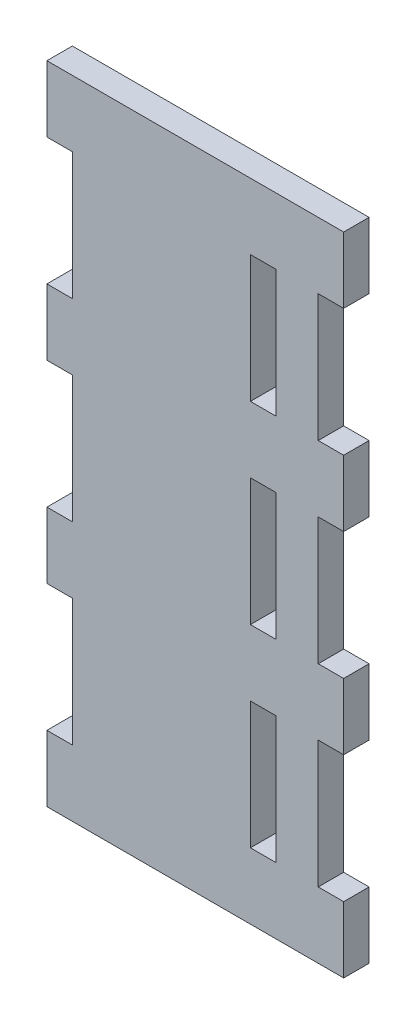
SolidWorks part; units mm, degrees
material "Oak"
ref_plane "Front Plane" through (0, 0, 0) normal (0, 0, 1) x (1, 0, 0)
ref_plane "Top Plane" through (0, 0, 0) normal (0, 1, 0) x (1, 0, 0)
ref_plane "Right Plane" through (0, 0, 0) normal (1, 0, 0) x (0, 0, -1)
sketch "Sketch1" plane through (0, 0, 0) normal (0, 0, 1) x (1, 0, 0)
  line L1 (-40.9935, 16.542) -> (-5.9935, 16.542)
  line L2 (-40.9935, 16.542) -> (-40.9935, -59.658)
  line L3 (-40.9935, -59.658) -> (-5.9935, -59.658)
  line L4 (-5.9935, 16.542) -> (-5.9935, -59.658)
  dimension "D1" = 76.2
  dimension "D2" = 35
extrude "Boss-Extrude1" add sketch "Sketch1" along normal blind 3
sketch "Sketch2" plane through (0, 0, 3) normal (0, 0, 1) x (1, 0, 0)
  line L0 (-40.9935, 16.542) -> (-40.9935, -59.658) construction
  line L1 (-40.9935, 8.742) -> (-37.9935, 8.742)
  line L2 (-40.9935, 8.742) -> (-40.9935, -6.258)
  line L3 (-40.9935, -6.258) -> (-37.9935, -6.258)
  line L4 (-37.9935, 8.742) -> (-37.9935, -6.258)
  line L5 (-5.9935, 16.542) -> (-40.9935, 16.542) construction
  line L6 (-5.9935, -59.658) -> (-5.9935, 16.542) construction
  line L7 (-5.9935, 8.742) -> (-8.9935, 8.742)
  line L8 (-5.9935, 8.742) -> (-5.9935, -6.258)
  line L9 (-5.9935, -6.258) -> (-8.9935, -6.258)
  line L10 (-8.9935, 8.742) -> (-8.9935, -6.258)
  point P8 (-39.4935, 8.742)
  dimension "D1" = 3
  dimension "D2" = 7.8
  dimension "D3" = 15
  dimension "D4" = 3
  dimension "D5" = 7.8
  dimension "D6" = 15
extrude "Cut-Extrude1" cut sketch "Sketch2" against normal through all
pattern_linear "LPattern1" count 3 spacing 22.8 along (0, -1, 0) of "Cut-Extrude1"
sketch "Sketch3" plane through (0, 0, 3) normal (0, 0, 1) x (1, 0, 0)
  line L0 (-40.9935, 16.542) -> (-40.9935, 8.742) construction
  line L1 (-16.9935, 8.742) -> (-13.9935, 8.742)
  line L2 (-16.9935, 8.742) -> (-16.9935, -6.258)
  line L3 (-16.9935, -6.258) -> (-13.9935, -6.258)
  line L4 (-13.9935, 8.742) -> (-13.9935, -6.258)
  line L5 (-5.9935, 16.542) -> (-40.9935, 16.542) construction
  dimension "D1" = 24
  dimension "D2" = 7.8
  dimension "D3" = 3
  dimension "D4" = 15
extrude "Cut-Extrude2" cut sketch "Sketch3" against normal through all
pattern_linear "LPattern2" count 3 spacing 22.8 along (0, -1, 0) of "Cut-Extrude2"
